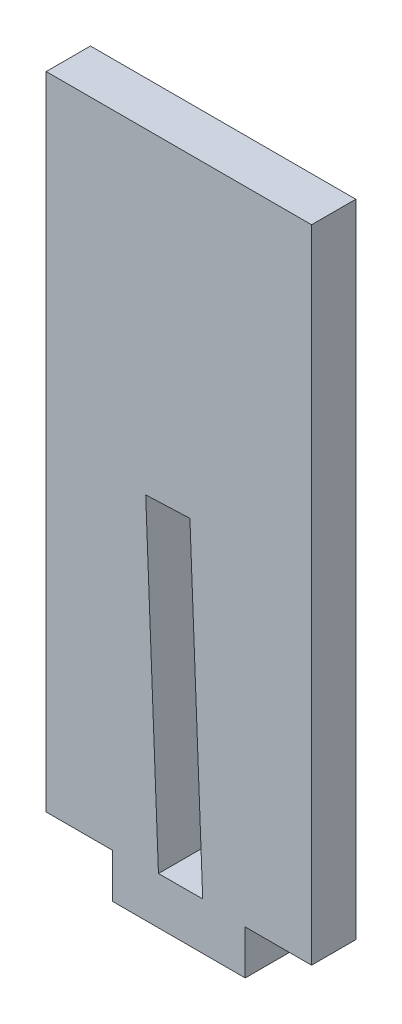
SolidWorks part; units mm, degrees
ref_plane "前视基准面" through (0, 0, 0) normal (0, 0, 1) x (1, 0, 0)
ref_plane "上视基准面" through (0, 0, 0) normal (0, 1, 0) x (1, 0, 0)
ref_plane "右视基准面" through (0, 0, 0) normal (1, 0, 0) x (0, 0, -1)
sketch "草图1" plane through (0, 0, 0) normal (0, 0, 1) x (1, 0, 0)
  line L0 (-6, 0) -> (-6, 15)
  line L1 (-6, 0) -> (-3, 0)
  line L3 (6, 0) -> (6, 15)
  line L4 (-3, 0) -> (-3, -2)
  line L6 (-3, -2) -> (3, -2)
  line L7 (3, 0) -> (3, -2)
  line L8 (-6, 15) -> (-6, 30.0788)
  line L9 (-6, 30.0788) -> (6, 30.0788)
  line L10 (6, 30.0788) -> (6, 15)
  line L11 (3, 0) -> (6, 0)
extrude "凸台-拉伸1" add sketch "草图1" along normal blind 2 contours L9 L10 L3 L11 L7 L6 L4 L1 L0 L8
sketch "草图3" plane through (0, 0, 2) normal (0, 0, 1) x (1, 0, 0)
  line L0 (17.7523, 29) -> (-31.8073, 29) construction
  line L1 (17.7523, 29) -> (-31.8073, 29)
  line L2 (10.2989, 29) -> (10.2989, 34.1435)
  line L3 (10.2989, 34.1435) -> (-9.585, 34.1435)
  line L4 (-9.585, 34.1435) -> (-9.585, 29)
  line M2 (-6, 30.0788) -> (-6, 0)
  line M8 (6, 0) -> (6, 30.0788)
  line M9 (6, 30.0788) -> (-6, 30.0788)
extrude "切除-拉伸2" cut sketch "草图3" against normal blind 10 contours L1 M8 M9 M2 | L3 L4 L1 L2 M2 M9 M8
sketch "草图4" plane through (0, 0, 2) normal (0, 0, 1) x (1, 0, 0)
  line L0 (-1.4882, 14.3645) -> (0.4981, 14.75)
  line L1 (-0.9242, 0.1291) -> (-1.4882, 14.3645)
  line L2 (1.0772, 0.1349) -> (0.4981, 14.75)
  line L3 (1.0772, 0.1349) -> (-0.9242, 0.1291)
  line L4 (1.0772, 0.1349) -> (-0.9242, 0.1291)
  line L5 (1.0772, 0.1349) -> (0.4981, 14.75)
  line L6 (-0.9242, 0.1291) -> (-1.4882, 14.3645)
  line L8 (0.4981, 14.75) -> (-1.5003, 14.6709)
  line L9 (-1.4882, 14.3645) -> (-1.5003, 14.6709)
extrude "切除-拉伸3" cut sketch "草图4" against normal blind 2
